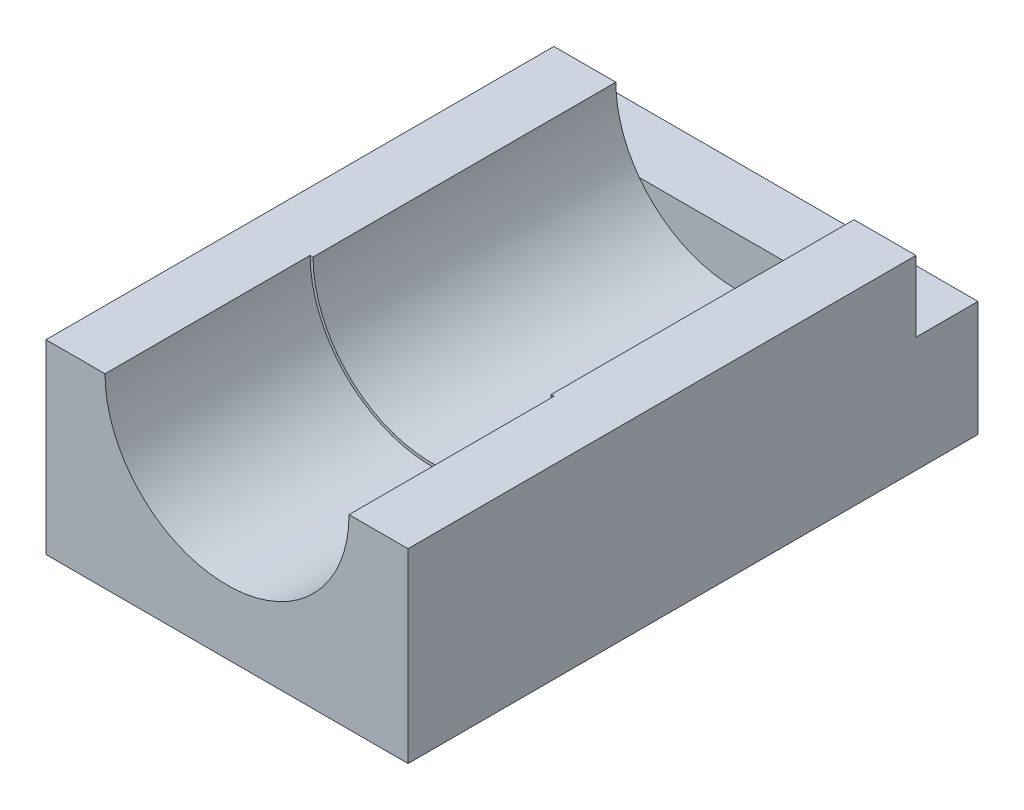
SolidWorks part; units mm, degrees
ref_plane "Front Plane" through (0, 0, 0) normal (0, 0, 1) x (1, 0, 0)
ref_plane "Top Plane" through (0, 0, 0) normal (0, 1, 0) x (1, 0, 0)
ref_plane "Right Plane" through (0, 0, 0) normal (1, 0, 0) x (0, 0, -1)
sketch "Sketch1" plane through (0, 0, 0) normal (0, 0, 1) x (1, 0, 0)
  line L7 (23.7638, 19.05) -> (23.7638, 0)
  line L10 (-13.3009, 19.05) -> (-13.3009, 0)
  line L12 (-13.3009, 19.05) -> (-6.9589, 19.05)
  line L13 (23.7638, 19.05) -> (17.4218, 19.05)
  line L14 (-13.3009, 0) -> (23.7638, 0)
  arc A1 (17.4218, 19.05) -> (-6.9589, 19.05) centre (5.2314, 19.05) cw
  dimension "D2" = 6.342
  dimension "D1" = 19.05
  dimension "D3" = 6.342
  dimension "D5" = 37.0648
extrude "Boss-Extrude1" add sketch "Sketch1" along normal blind 31
sketch "Sketch3" plane through (0, 0, 31) normal (0, 0, 1) x (1, 0, 0)
  line L1 (-13.3009, 19.05) -> (-13.3009, 0)
  line L3 (-13.3009, 0) -> (23.7638, 0)
  line L14 (-13.3009, 19.05) -> (-7.2589, 19.05)
  line L15 (-6.9589, 19.05) -> (-13.3009, 19.05) construction
  line L16 (17.7218, 19.05) -> (23.7638, 19.05)
  line L17 (23.7638, 19.05) -> (23.7638, 0)
  arc A0 (17.7218, 19.05) -> (-7.2589, 19.05) centre (5.2314, 19.05) cw
  point P3 (-7.2589, 19.05)
  point P8 (0, 0)
  dimension "D1" = 6.042
  dimension "D2" = 19.05
  dimension "D4" = 37.0648
extrude "Boss-Extrude2" add sketch "Sketch3" along normal blind 21
sketch "Sketch6" plane through (0, 0, 0) normal (0, 0, -1) x (-1, 0, 0)
  line L0 (-23.7638, 0) -> (13.3009, 0)
  line L1 (13.3009, 0) -> (13.3009, 11.8004)
  line L2 (13.3009, 19.05) -> (13.3009, 0) construction
  line L3 (13.3009, 11.8004) -> (-23.7638, 11.8004)
  line L4 (-23.7638, 0) -> (-23.7638, 19.05) construction
  line L5 (-23.7638, 11.8004) -> (-23.7638, 0)
extrude "Boss-Extrude3" add sketch "Sketch6" along normal blind 6.35
sketch "Sketch8" plane through (0, 0, 0) normal (0, -1, 0) x (1, 0, 0)
  line L0 (-13.3009, 52) -> (23.7638, 52) construction
  line L1 (-13.3009, 52) -> (-13.3009, -6.35) construction
  line L2 (23.7638, 52) -> (23.7638, -6.35) construction
  line L3 (23.7638, -6.35) -> (-13.3009, -6.35) construction
  circle A0 centre (-6.9509, 45.65) radius 2
  circle A1 centre (-6.9509, 0) radius 2
  circle A2 centre (17.4138, 45.65) radius 2
  circle A3 centre (17.4138, 0) radius 2
  dimension "D1" = 4
  dimension "D2" = 4
  dimension "D3" = 4
  dimension "D4" = 4
  dimension "D5" = 6.35
  dimension "D6" = 6.35
  dimension "D7" = 6.35
  dimension "D8" = 6.35
  dimension "D9" = 6.35
  dimension "D10" = 6.35
  dimension "D11" = 6.35
  dimension "D12" = 6.35
extrude "Cut-Extrude4" cut sketch "Sketch8" against normal blind 7
